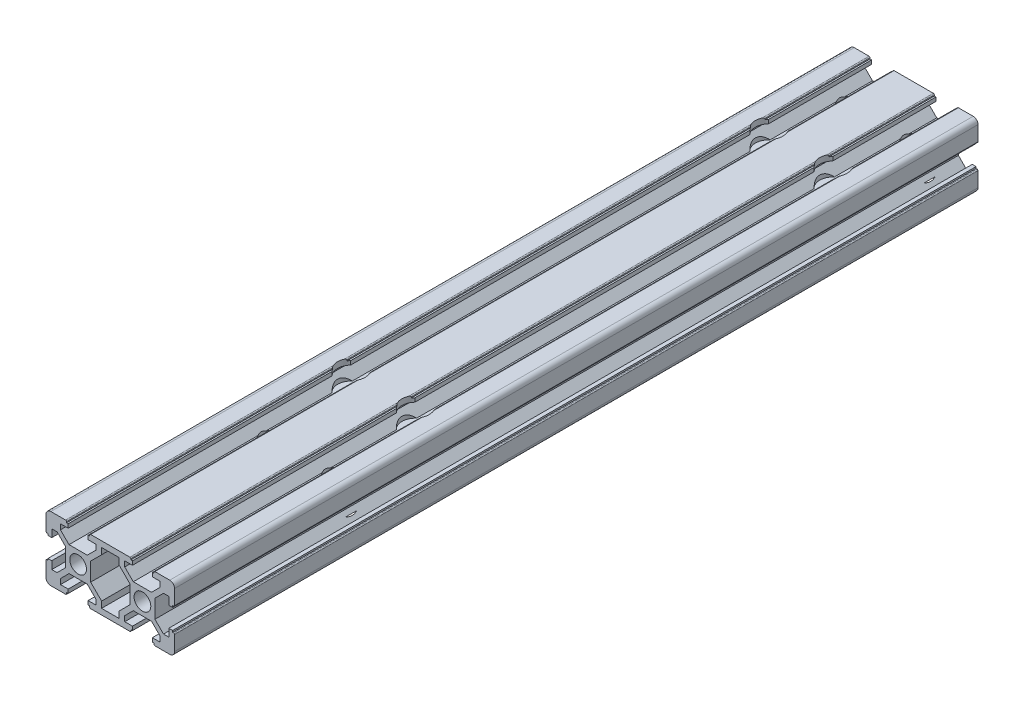
SolidWorks part; units mm, degrees
ref_plane "前视基准面" through (0, 0, 0) normal (0, 0, 1) x (1, 0, 0)
ref_plane "上视基准面" through (0, 0, 0) normal (0, 1, 0) x (1, 0, 0)
ref_plane "右视基准面" through (0, 0, 0) normal (1, 0, 0) x (0, 0, -1)
sketch "草图1" plane through (0, 0, 0) normal (0, 0, 1) x (1, 0, 0)
  line L0 (0, 0) -> (0, -41497.3383) construction
  line L1 (0, 0) -> (41497.3383, 0) construction
  line L2 (-13.9, 0) -> (-13.9, 2.8393)
  line L3 (-13.9, 2.8393) -> (-16.5607, 5.5)
  line L4 (-16.5607, 5.5) -> (-18.2, 5.5)
  line L5 (-18.2, 5.5) -> (-18.2, 3.1)
  line L6 (-18.2, 3.1) -> (-19.4, 3.1)
  line L7 (-19.4, 3.1) -> (-19.4, 3.6)
  line L8 (-19.4, 3.6) -> (-20, 3.6)
  line L9 (-20, 3.6) -> (-20, 10)
  line L10 (-20, 10) -> (-13.6, 10)
  line L11 (-13.6, 10) -> (-13.6, 9.4)
  line L12 (-13.6, 9.4) -> (-13.1, 9.4)
  line L13 (-13.1, 9.4) -> (-13.1, 8.2)
  line L14 (-13.1, 8.2) -> (-15.5, 8.2)
  line L15 (-15.5, 6.5607) -> (-12.8393, 3.9)
  line L16 (-12.8393, 3.9) -> (-7.1607, 3.9)
  line L17 (-4.5, 6.5607) -> (-7.1607, 3.9)
  line L18 (-4.5, 6.5607) -> (-4.5, 8.2)
  line L19 (-4.5, 8.2) -> (-6.9, 8.2)
  line L20 (-6.9, 8.2) -> (-6.9, 9.4)
  line L21 (-6.9, 9.4) -> (-6.4, 9.4)
  line L22 (-6.4, 9.4) -> (-6.4, 10)
  line L23 (-6.4, 10) -> (6.4, 10)
  line L24 (-15.5, 8.2) -> (-15.5, 6.5607)
  line L25 (-10, 0) -> (-20, 10) construction
  line L26 (-6.1, -2.8393) -> (-6.1, 2.8393)
  line L27 (-6.1, 2.8393) -> (-2.7, 6.2393)
  line L28 (-2.7, 6.2393) -> (-2.7, 8.2)
  line L29 (-2.7, 8.2) -> (2.7, 8.2)
  line L30 (-10, 0) -> (0, 10) construction
  line L31 (13.9, 0) -> (13.9, 2.8393)
  line L32 (6.1, -2.8393) -> (6.1, 2.8393)
  line L33 (4.5, 6.5607) -> (7.1607, 3.9)
  line L34 (12.8393, 3.9) -> (7.1607, 3.9)
  line L35 (6.1, 2.8393) -> (2.7, 6.2393)
  line L36 (2.7, 6.2393) -> (2.7, 8.2)
  line L37 (4.5, 6.5607) -> (4.5, 8.2)
  line L38 (6.4, 9.4) -> (6.4, 10)
  line L39 (6.9, 9.4) -> (6.4, 9.4)
  line L40 (6.9, 8.2) -> (6.9, 9.4)
  line L41 (4.5, 8.2) -> (6.9, 8.2)
  line L42 (13.1, 9.4) -> (13.1, 8.2)
  line L43 (13.6, 9.4) -> (13.1, 9.4)
  line L44 (13.6, 10) -> (13.6, 9.4)
  line L45 (20, 10) -> (13.6, 10)
  line L46 (20, 3.6) -> (20, 10)
  line L47 (19.4, 3.6) -> (20, 3.6)
  line L48 (19.4, 3.1) -> (19.4, 3.6)
  line L49 (18.2, 3.1) -> (19.4, 3.1)
  line L50 (18.2, 5.5) -> (18.2, 3.1)
  line L51 (16.5607, 5.5) -> (18.2, 5.5)
  line L52 (13.9, 2.8393) -> (16.5607, 5.5)
  line L53 (15.5, 6.5607) -> (12.8393, 3.9)
  line L54 (15.5, 8.2) -> (15.5, 6.5607)
  line L55 (13.1, 8.2) -> (15.5, 8.2)
  line L56 (15.5, -6.5607) -> (12.8393, -3.9)
  line L57 (13.9, -2.8393) -> (16.5607, -5.5)
  line L58 (16.5607, -5.5) -> (18.2, -5.5)
  line L59 (18.2, -5.5) -> (18.2, -3.1)
  line L60 (18.2, -3.1) -> (19.4, -3.1)
  line L61 (19.4, -3.1) -> (19.4, -3.6)
  line L62 (19.4, -3.6) -> (20, -3.6)
  line L63 (12.8393, -3.9) -> (7.1607, -3.9)
  line L64 (13.9, 0) -> (13.9, -2.8393)
  line L65 (13.1, -8.2) -> (15.5, -8.2)
  line L66 (15.5, -8.2) -> (15.5, -6.5607)
  line L67 (20, -3.6) -> (20, -10)
  line L68 (20, -10) -> (13.6, -10)
  line L69 (13.6, -10) -> (13.6, -9.4)
  line L70 (13.6, -9.4) -> (13.1, -9.4)
  line L71 (13.1, -9.4) -> (13.1, -8.2)
  line L72 (4.5, -8.2) -> (6.9, -8.2)
  line L73 (6.9, -8.2) -> (6.9, -9.4)
  line L74 (6.9, -9.4) -> (6.4, -9.4)
  line L75 (6.4, -9.4) -> (6.4, -10)
  line L76 (4.5, -6.5607) -> (4.5, -8.2)
  line L77 (2.7, -6.2393) -> (2.7, -8.2)
  line L78 (6.1, -2.8393) -> (2.7, -6.2393)
  line L79 (4.5, -6.5607) -> (7.1607, -3.9)
  line L80 (-2.7, -8.2) -> (2.7, -8.2)
  line L81 (-2.7, -6.2393) -> (-2.7, -8.2)
  line L82 (-6.1, -2.8393) -> (-2.7, -6.2393)
  line L83 (-4.5, -6.5607) -> (-7.1607, -3.9)
  line L84 (-4.5, -8.2) -> (-6.9, -8.2)
  line L85 (-4.5, -6.5607) -> (-4.5, -8.2)
  line L86 (-6.4, -10) -> (6.4, -10)
  line L87 (-6.4, -9.4) -> (-6.4, -10)
  line L88 (-6.9, -9.4) -> (-6.4, -9.4)
  line L89 (-6.9, -8.2) -> (-6.9, -9.4)
  line L90 (-13.1, -9.4) -> (-13.1, -8.2)
  line L91 (-13.6, -9.4) -> (-13.1, -9.4)
  line L92 (-13.6, -10) -> (-13.6, -9.4)
  line L93 (-15.5, -8.2) -> (-15.5, -6.5607)
  line L94 (-13.1, -8.2) -> (-15.5, -8.2)
  line L95 (-12.8393, -3.9) -> (-7.1607, -3.9)
  line L96 (-15.5, -6.5607) -> (-12.8393, -3.9)
  line L97 (-13.9, 0) -> (-13.9, -2.8393)
  line L98 (-13.9, -2.8393) -> (-16.5607, -5.5)
  line L99 (-19.4, -3.6) -> (-20, -3.6)
  line L100 (-19.4, -3.1) -> (-19.4, -3.6)
  line L101 (-18.2, -3.1) -> (-19.4, -3.1)
  line L102 (-18.2, -5.5) -> (-18.2, -3.1)
  line L103 (-16.5607, -5.5) -> (-18.2, -5.5)
  line L104 (-20, -3.6) -> (-20, -10)
  line L105 (-20, -10) -> (-13.6, -10)
  circle A0 centre (-10, 0) radius 2.6
  circle A1 centre (10, 0) radius 2.6
  point P50 (0, 8.2)
  point P95 (6.1, 0)
  point P96 (-6.1, 0)
  dimension "D1" = 5.2
  dimension "D2" = 45
  dimension "D3" = 1.5
  dimension "D4" = 20
  dimension "D5" = 40
  dimension "D6" = 0.75
  dimension "D7" = 7.2
  dimension "D8" = 6.2
  dimension "D9" = 6.1
  dimension "D10" = 1.8
  dimension "D11" = 1.2
  dimension "D12" = 12.2
  dimension "D13" = 5.4
  dimension "D14" = 11
  dimension "D15" = 1.5
  dimension "D16" = 0.75
extrude "凸台-拉伸1" add sketch "草图1" along normal mid plane 250
fillet "圆角1" radius 1.5 4 edges at (20, -10, 0) (20, 10, 0) (-20, -10, 0) (-20, 10, 0)
fillet "圆角2" radius 0.3 12 edges at (-6.4, 10, 0) (-13.6, 10, 0) (-20, 3.6, 0) (-20, -3.6, 0) (-13.6, -10, 0) (-6.4, -10, 0) (6.4, -10, 0) (20, -3.6, 0) (20, 3.6, 0) (13.6, -10, 0) (13.6, 10, 0) (6.4, 10, 0)
sketch "草图3" plane through (0, -3.9, 0) normal (0, -1, 0) x (1, 0, 0)
  line L0 (-10, -90) -> (10, -90) construction
  line L1 (-10, -45) -> (10, -45) construction
  line L2 (-6.1, -125) -> (6.1, -125) construction
  line L3 (10, -5) -> (-10, -5) construction
  line L4 (10, 40) -> (-10, 40) construction
  line L5 (12.8393, -125) -> (7.1607, -125) construction
  line L6 (10, -115) -> (-10, -115) construction
  circle A0 centre (-10, -90) radius 2.1
  circle A1 centre (10, -90) radius 2.1
  circle A2 centre (10, 40) radius 2.1
  circle A3 centre (-10, 40) radius 2.1
  circle A4 centre (-10, -45) radius 2.1
  circle A5 centre (10, -45) radius 2.1
  circle A6 centre (10, -5) radius 2.1
  circle A7 centre (-10, -5) radius 2.1
  circle A8 centre (10, -115) radius 3.1
  circle A9 centre (-10, -115) radius 3.1
  circle A10 centre (10, 65) radius 3.1
  circle A11 centre (-10, 65) radius 3.1
  point P4 (0, 40)
  point P5 (0, -90)
  point P9 (0, -5)
  point P18 (0, -45)
  point P29 (0, -115)
  dimension "D1" = 4.2
  dimension "D2" = 20
  dimension "D4" = 45
  dimension "D7" = 10
  dimension "D8" = 6.2
  dimension "D11" = 180
  dimension "D3" = 35
  dimension "D5" = 40
  dimension "D6" = 45
  dimension "D9" = 20
  dimension "D10" = 2
extrude "切除-拉伸1" cut sketch "草图3" against normal through all both and the other way through all
sketch "草图4" plane through (0, 3.9, 0) normal (0, 1, 0) x (1, 0, 0)
  circle A0 centre (-10, -40) radius 4.25
  circle A1 centre (10, -40) radius 4.25
  circle A2 centre (-10, 90) radius 4.25
  circle A3 centre (10, 90) radius 4.25
  dimension "D1" = 8.5
extrude "切除-拉伸2" cut sketch "草图4" along normal through all
sketch "草图5" plane through (0, -3.9, 0) normal (0, -1, 0) x (1, 0, 0)
  circle A0 centre (10, -115) radius 5.25
  circle A1 centre (-10, -115) radius 5.25
  circle A2 centre (10, 65) radius 5.25
  circle A3 centre (-10, 65) radius 5.25
  dimension "D1" = 10.5
extrude "切除-拉伸3" cut sketch "草图5" along normal through all
equation "\"D6@草图1\"=1/2*\"D3@草图1\""
equation "\"D16@草图1\"=0.5*\"D15@草图1\""
